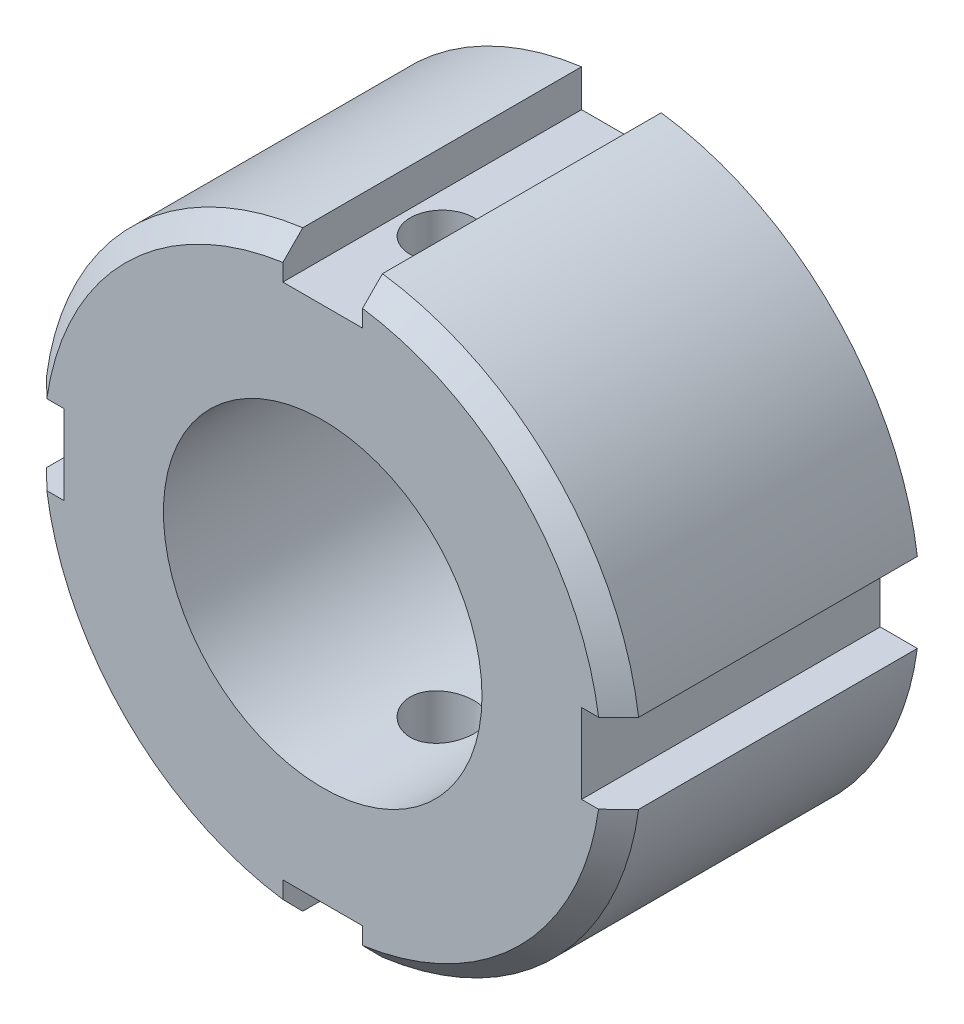
SolidWorks part; units mm, degrees
ref_plane "Front Plane" through (0, 0, 0) normal (0, 0, 1) x (1, 0, 0)
ref_plane "Top Plane" through (0, 0, 0) normal (0, 1, 0) x (1, 0, 0)
ref_plane "Right Plane" through (0, 0, 0) normal (1, 0, 0) x (0, 0, -1)
sketch "Sketch1" plane through (0, 0, 0) normal (0, 0, 1) x (1, 0, 0)
  circle A0 centre (0, 0) radius 15
  circle A1 centre (0, 0) radius 8
  dimension "D1" = 30
  dimension "D2" = 16
extrude "Boss-Extrude1" add sketch "Sketch1" along normal blind 15
sketch "Sketch2" plane through (0, 0, 15) normal (0, 0, 1) x (1, 0, 0)
  line L0 (0, 0) -> (0, 18.3019) construction
  line L1 (13, 2) -> (17, 2)
  line L2 (-2, 13) -> (2, 13)
  line L3 (-2, 13) -> (-2, 17)
  line L4 (-2, 17) -> (2, 17)
  line L5 (2, 13) -> (2, 17)
  line L6 (-2, 13) -> (2, 17) construction
  line L7 (-2, 17) -> (2, 13) construction
  line L8 (13, 2) -> (13, -2)
  line L9 (13, -2) -> (17, -2)
  line L10 (17, 2) -> (17, -2)
  line L11 (2, -13) -> (2, -17)
  line L12 (2, -13) -> (-2, -13)
  line L13 (-2, -13) -> (-2, -17)
  line L14 (2, -17) -> (-2, -17)
  line L15 (-13, -2) -> (-17, -2)
  line L16 (-13, -2) -> (-13, 2)
  line L17 (-13, 2) -> (-17, 2)
  line L18 (-17, -2) -> (-17, 2)
  circle A0 centre (0, 0) radius 18.3019 construction
  circle A1 centre (0, 0) radius 15 construction
  circle A2 centre (0, 0) radius 18.3019 construction
  circle A3 centre (0, 0) radius 18.3019 construction
  circle A4 centre (0, 0) radius 18.3019 construction
  point P4 (0, 15)
  point P29 (0, 0)
  dimension "D1" = 4
  dimension "D2" = 2
  dimension "D3" = 4
extrude "Cut-Extrude1" cut sketch "Sketch2" against normal through all
chamfer "Chamfer1" distance 1 angle 45 4 edges at (10.6066, -10.6066, 15) (-10.6066, -10.6066, 15) (-10.6066, 10.6066, 15) (10.6066, 10.6066, 15)
sketch "Sketch3" plane through (0, 13, 0) normal (0, 1, 0) x (1, 0, 0)
  line L0 (-2, -15) -> (2, -15) construction
  circle A0 centre (0, -9) radius 1.6005
  dimension "D1" = 6
extrude "Cut-Extrude2" cut sketch "Sketch3" against normal through all
